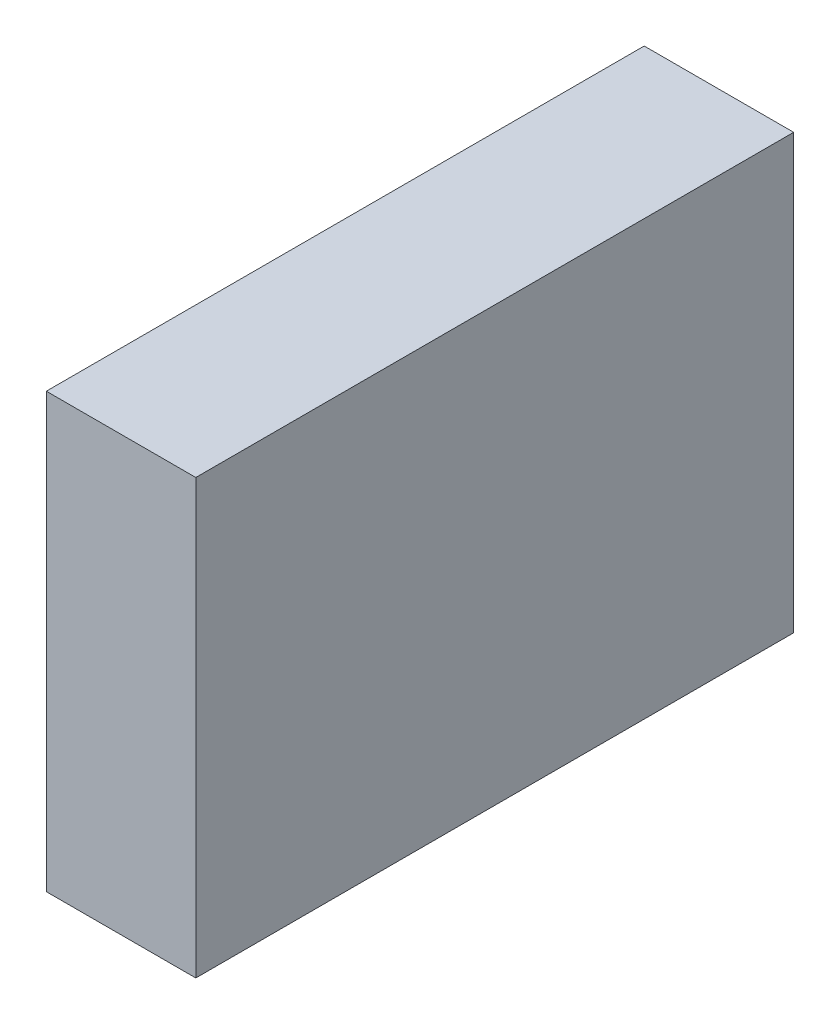
SolidWorks part; units mm, degrees
ref_plane "Front Plane" through (0, 0, 0) normal (0, 0, 1) x (1, 0, 0)
ref_plane "Top Plane" through (0, 0, 0) normal (0, 1, 0) x (1, 0, 0)
ref_plane "Right Plane" through (0, 0, 0) normal (1, 0, 0) x (0, 0, -1)
sketch "Sketch1" plane through (0, 0, 0) normal (1, 0, 0) x (0, 0, -1)
  line L1 (0, 0) -> (40, 0)
  line L2 (0, 0) -> (0, 29)
  line L3 (0, 29) -> (40, 29)
  line L4 (40, 0) -> (40, 29)
extrude "Boss-Extrude1" add sketch "Sketch1" along normal blind 10
